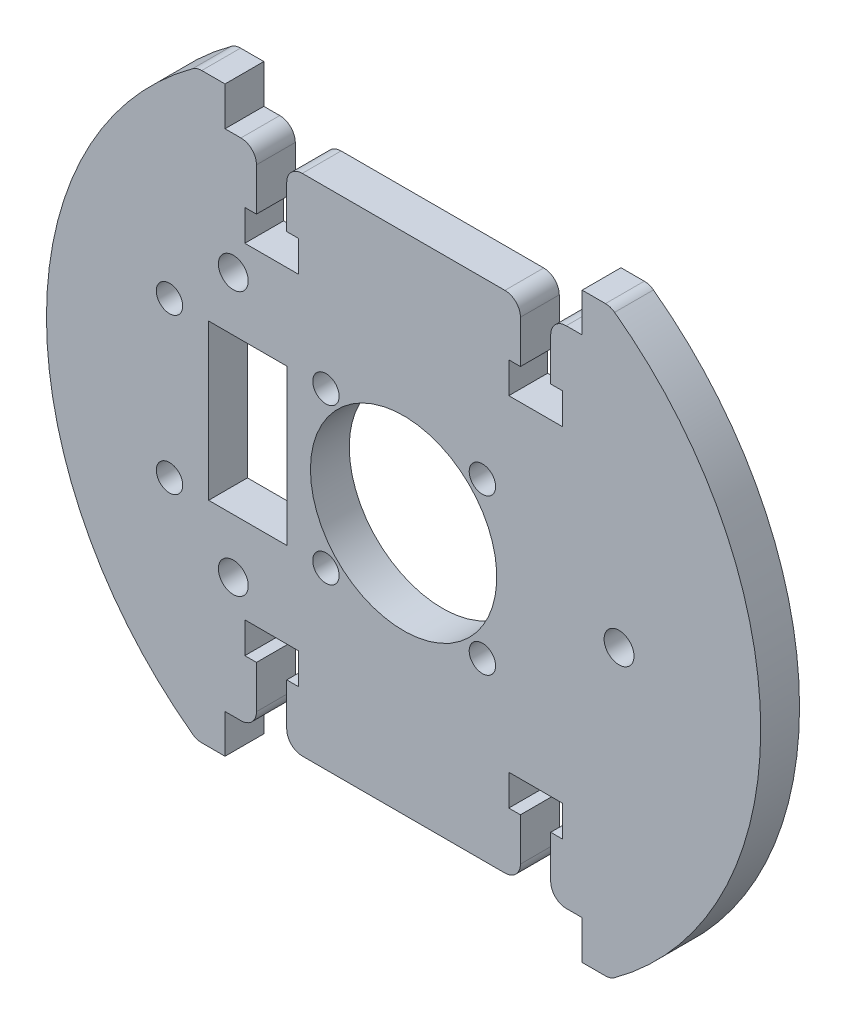
SolidWorks part; units mm, degrees
ref_plane "Plan de face" through (0, 0, 0) normal (0, 0, 1) x (1, 0, 0)
ref_plane "Plan de dessus" through (0, 0, 0) normal (0, 1, 0) x (1, 0, 0)
ref_plane "Plan de droite" through (0, 0, 0) normal (1, 0, 0) x (0, 0, -1)
sketch "Esquisse1" plane through (0, 0, 0) normal (0, 0, 1) x (1, 0, 0)
  line L0 (-21.9331, -17) -> (-21.9331, 17) construction
  line L1 (14.5, 5) -> (14.5, -5) construction
  line L2 (0, 0) -> (-21.9331, 0) construction
  line L3 (18.95, 30.5) -> (15.05, 30.5) construction
  line L4 (17, 21) -> (17, 30.5) construction
  line L5 (13.05, 32.5) -> (-13.05, 32.5)
  line L6 (15.05, 30.5) -> (15.05, 25)
  line L7 (15.05, 25) -> (13.55, 25)
  line L8 (13.55, 25) -> (13.55, 21)
  line L9 (26, -37.4976) -> (23, -37.5)
  line L10 (23, -37.5) -> (23, -32.5)
  line L11 (23, -32.5) -> (20.95, -32.5)
  line L12 (18.95, -25) -> (18.95, -30.5)
  line L13 (20.45, -25) -> (18.95, -25)
  line L14 (20.45, -21) -> (20.45, -25)
  line L15 (13.55, -21) -> (20.45, -21)
  line L16 (13.55, -25) -> (13.55, -21)
  line L17 (15.05, -25) -> (13.55, -25)
  line L18 (15.05, -30.5) -> (15.05, -25)
  line L19 (13.05, -32.5) -> (-13.05, -32.5)
  line L20 (17, -21) -> (17, -30.5) construction
  line L21 (18.95, -30.5) -> (15.05, -30.5) construction
  line L22 (0, 0) -> (46, 0) construction
  line L23 (13.55, 21) -> (20.45, 21)
  line L24 (20.45, 21) -> (20.45, 25)
  line L25 (20.45, 25) -> (18.95, 25)
  line L26 (18.95, 25) -> (18.95, 30.5)
  line L27 (23, 32.5) -> (20.95, 32.5)
  line L28 (23, 37.5) -> (23, 32.5)
  line L29 (26, 37.4976) -> (23, 37.5)
  line L30 (-18.95, -30.5) -> (-15.05, -30.5) construction
  line L31 (-17, -21) -> (-17, -30.5) construction
  line L32 (-15.05, -30.5) -> (-15.05, -25)
  line L33 (-15.05, -25) -> (-13.55, -25)
  line L34 (-13.55, -25) -> (-13.55, -21)
  line L35 (-13.55, -21) -> (-20.45, -21)
  line L36 (-20.45, -21) -> (-20.45, -25)
  line L37 (-20.45, -25) -> (-18.95, -25)
  line L38 (-18.95, -25) -> (-18.95, -30.5)
  line L39 (-23, -32.5) -> (-20.95, -32.5)
  line L40 (-23, -37.5) -> (-23, -32.5)
  line L41 (10.15, -10) -> (10.15, -2.6)
  line L42 (10.15, 2.6) -> (10.15, 10)
  line L43 (10.15, 10) -> (-30.15, 10)
  line L44 (-30.15, 10) -> (-30.15, 2.6)
  line L45 (-30.15, -2.6) -> (-30.15, -10)
  line L46 (-30.15, -10) -> (10.15, -10)
  line L47 (-26, -37.4976) -> (-23, -37.5)
  line L48 (-36.5, -0.6) -> (-32.15, -0.6)
  line L49 (12.15, -0.6) -> (16.5, -0.6)
  line L50 (-36.5, 0.6) -> (-32.15, 0.6)
  line L51 (12.15, 0.6) -> (16.5, 0.6)
  line L52 (-17, 21) -> (-17, 30.5) construction
  line L53 (-18.95, 30.5) -> (-15.05, 30.5) construction
  line L54 (-26, 37.4976) -> (-23, 37.5)
  line L55 (-23, 37.5) -> (-23, 32.5)
  line L56 (0, -32.5) -> (0, 32.5) construction
  line L57 (-23, 32.5) -> (-20.95, 32.5)
  line L58 (-18.95, 25) -> (-18.95, 30.5)
  line L59 (-20.45, 25) -> (-18.95, 25)
  line L60 (-20.45, 21) -> (-20.45, 25)
  line L61 (-13.55, 21) -> (-20.45, 21)
  line L62 (-13.55, 25) -> (-13.55, 21)
  line L63 (-15.05, 25) -> (-13.55, 25)
  line L64 (-15.05, 30.5) -> (-15.05, 25)
  circle A0 centre (27.75, 0) radius 1.925
  circle A1 centre (-21.9331, -17) radius 1.925
  circle A2 centre (-21.9331, 17) radius 1.925
  arc A3 (16.5, 0.6) -> (16.5, -0.6) centre (16.5, 0) cw
  arc A4 (27.1802, -37.1112) -> (27.1802, 37.1112) centre (0, 0) ccw
  arc A5 (-36.5, 0.6) -> (-36.5, -0.6) centre (-36.5, 0) ccw
  arc A6 (13.05, 32.5) -> (15.05, 30.5) centre (13.05, 30.5) cw
  arc A7 (26, -37.4976) -> (27.1802, -37.1112) centre (25.9984, -35.4976) ccw
  arc A8 (18.95, -30.5) -> (20.95, -32.5) centre (20.95, -30.5) ccw
  arc A9 (13.05, -32.5) -> (15.05, -30.5) centre (13.05, -30.5) ccw
  arc A10 (18.95, 30.5) -> (20.95, 32.5) centre (20.95, 30.5) cw
  arc A11 (26, 37.4976) -> (27.1802, 37.1112) centre (25.9984, 35.4976) cw
  arc A12 (-13.05, -32.5) -> (-15.05, -30.5) centre (-13.05, -30.5) cw
  arc A13 (-18.95, -30.5) -> (-20.95, -32.5) centre (-20.95, -30.5) cw
  arc A14 (-26, -37.4976) -> (-27.1802, -37.1112) centre (-25.9984, -35.4976) cw
  arc A15 (-27.1802, -37.1112) -> (-27.1802, 37.1112) centre (0, 0) cw
  arc A16 (-26, 37.4976) -> (-27.1802, 37.1112) centre (-25.9984, 35.4976) ccw
  arc A17 (-18.95, 30.5) -> (-20.95, 32.5) centre (-20.95, 30.5) ccw
  circle A18 centre (14.5, -5) radius 1.925
  circle A19 centre (14.5, 5) radius 1.925
  circle A20 centre (-34.5, -5) radius 1.925
  circle A21 centre (-34.5, 5) radius 1.925
  arc A22 (12.15, -0.6) -> (10.15, -2.6) centre (12.15, -2.6) ccw
  arc A23 (-13.05, 32.5) -> (-15.05, 30.5) centre (-13.05, 30.5) ccw
  arc A24 (-30.15, -2.6) -> (-32.15, -0.6) centre (-32.15, -2.6) ccw
  arc A27 (-32.15, 0.6) -> (-30.15, 2.6) centre (-32.15, 2.6) ccw
  arc A28 (10.15, 2.6) -> (12.15, 0.6) centre (12.15, 2.6) ccw
  dimension "D5" = 3.85
  dimension "D6" = 46
  dimension "D7" = 34
  dimension "D8" = 2
  dimension "D13" = 2
  dimension "D14" = 2
  dimension "D23" = 4.35
  dimension "D25" = 2
  dimension "D28" = 5
  dimension "D32" = 2
  dimension "D2" = 32.5
  dimension "D3" = 20
  dimension "D4" = 10
  dimension "D9" = 11.5
  dimension "D10" = 7.5
  dimension "D11" = 6.9
  dimension "D12" = 3.9
  dimension "D15" = 13.55
  dimension "D16" = 5.5
  dimension "D17" = 10.15
  dimension "D18" = 40.3
  dimension "D19" = 4.35
  dimension "D20" = 4.35
  dimension "D21" = 1.2
  dimension "D22" = 0.6
  dimension "D24" = 6.35
  dimension "D26" = 21.9331
  dimension "D27" = 10
  dimension "D29" = 10
  dimension "D30" = 4.35
  dimension "D31" = 6.35
  dimension "D33" = 27.75
  dimension "D34" = 2
  dimension "D35" = 5.2
  dimension "D36" = 2.6
  dimension "D37" = 5
  dimension "D38" = 6
  dimension "D39" = 3
extrude "Boss.-Extru.1" add sketch "Esquisse1" along normal blind 5
sketch "草图1" plane through (0, 0, 0) normal (0, 0, -1) x (-1, 0, 0)
  line L0 (30.15, 2.6) -> (30.15, -2.6)
  line L1 (-10.15, 2.6) -> (-10.15, -2.6)
  line L2 (-10.15, -2.6) -> (-17.8155, -2.6)
  line L3 (-17.8155, -2.6) -> (-17.8155, 2.6)
  line L4 (-17.8155, 2.6) -> (-10.15, 2.6)
  line L5 (30.15, 2.6) -> (38.1609, 2.6)
  line L6 (38.1609, 2.6) -> (38.1609, -2.6)
  line L7 (38.1609, -2.6) -> (30.15, -2.6)
extrude "凸台-拉伸1" add sketch "草图1" against normal blind 5
sketch "草图2" plane through (0, 0, 0) normal (0, 0, -1) x (-1, 0, 0)
  line L0 (-10.15, 10) -> (-18.0785, 10)
  line L1 (-18.0785, 10) -> (-18.0785, -9.5613)
  line L2 (-18.0785, -9.5613) -> (-10.15, -10)
  line L3 (30.15, 10) -> (38.6353, 10)
  line L4 (38.6353, 10) -> (38.6353, -10)
  line L5 (38.6353, -10) -> (30.15, -10)
  line L6 (30.15, 10) -> (30.15, -10) construction
  line L7 (30.15, -10) -> (30.15, 10)
  line L8 (-10.15, 10) -> (-10.15, -10)
extrude "凸台-拉伸2" add sketch "草图2" against normal blind 5
sketch "草图3" plane through (0, 0, 0) normal (0, 0, -1) x (-1, 0, 0)
  line L0 (30.15, -10) -> (-10.15, -10) construction
  line L1 (-10.15, 10) -> (30.15, 10) construction
  circle A0 centre (30.15, 10) radius 1.6
  circle A1 centre (30.15, -10) radius 1.6
  circle A2 centre (-10.15, 10) radius 1.6
  circle A3 centre (-10.15, -10) radius 1.6
  circle A4 centre (10, -10) radius 1.6
  circle A5 centre (10, 10) radius 1.6
extrude "切除-拉伸1" cut sketch "草图3" against normal blind 5
sketch "草图5" plane through (0, 0, 0) normal (0, 0, -1) x (-1, 0, 0)
  line L0 (30.15, 8.4) -> (30.15, -8.4)
  line L1 (28.55, -10) -> (11.6, -10)
  line L2 (8.4, -10) -> (-8.55, -10)
  line L3 (-10.15, -8.4) -> (-10.15, 8.4)
  line L4 (-8.55, 10) -> (8.4, 10)
  line L5 (11.6, 10) -> (28.55, 10)
  circle A0 centre (-10.15, 10) radius 1.6
  circle A1 centre (10, 10) radius 1.6
  circle A2 centre (-10.15, -10) radius 1.6
  circle A3 centre (10, -10) radius 1.6
  circle A4 centre (30.15, -10) radius 1.6
  circle A5 centre (30.15, 10) radius 1.6
extrude "凸台-拉伸3" add sketch "草图5" against normal blind 5 contours A5 L5 A1 L4 A0 L3 A2 L2 A3 L1 A4 L0
sketch "草图6" plane through (0, 0, 0) normal (0, 0, -1) x (-1, 0, 0)
  line L0 (-10.15, 10) -> (10, 10)
  line L1 (10, 10) -> (30.15, 10)
  line L2 (30.15, 10) -> (30.15, -10)
  line L3 (30.15, -10) -> (10, -10)
  line L4 (10, -10) -> (-10.15, -10)
  line L5 (-10.15, -10) -> (-10.15, 10)
  line L6 (10, 10) -> (10, -10)
  line L8 (20.075, 10) -> (20.075, -10)
  line L11 (25.1125, -5) -> (25.1125, 5)
  line L12 (25.1125, 5) -> (25.1125, 10)
  line L14 (10, -10) -> (9.9994, -9.9466)
  line L16 (15.0375, 5) -> (15.0375, -5)
  line L17 (15.0375, -5) -> (15.0375, -10)
  line L18 (15.0375, 5) -> (15.0375, 10)
  line L19 (25.1125, -5) -> (25.1125, -10)
  circle A0 centre (0, 0) radius 12
extrude "切除-拉伸2" cut sketch "草图6" against normal blind 5 contours L0 A0 | L6 A0 L0 L5 L4 | L6 A0 | L5 A0 | L4 A0 | L18 L16 L17 L3 L8 L1 | L19 L11 L12 L1 L8 L3
sketch "草图7" plane through (0, 0, 0) normal (0, 0, -1) x (-1, 0, 0)
  circle A0 centre (-10.15, 10) radius 1.7
  circle A1 centre (10, 10) radius 1.7
  circle A2 centre (-10.15, -10) radius 1.7
  circle A3 centre (10, -10) radius 1.7
  circle A4 centre (30.15, -10) radius 1.7
  circle A5 centre (30.15, 10) radius 1.7
  circle A6 centre (0, 0) radius 11
extrude "切除-拉伸3" cut sketch "草图7" against normal blind 5
